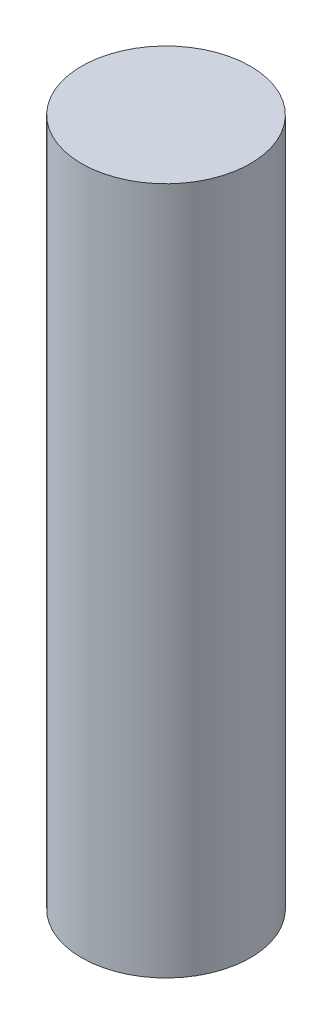
SolidWorks part; units mm, degrees
ref_plane "Front Plane" through (0, 0, 0) normal (0, 0, 1) x (1, 0, 0)
ref_plane "Top Plane" through (0, 0, 0) normal (0, 1, 0) x (1, 0, 0)
ref_plane "Right Plane" through (0, 0, 0) normal (1, 0, 0) x (0, 0, -1)
sketch "Sketch1" plane through (0, 0, 0) normal (0, 1, 0) x (1, 0, 0)
  circle A0 centre (0, 0) radius 13.5
  dimension "D1" = 27
extrude "Boss-Extrude1" add sketch "Sketch1" along normal mid plane 110
